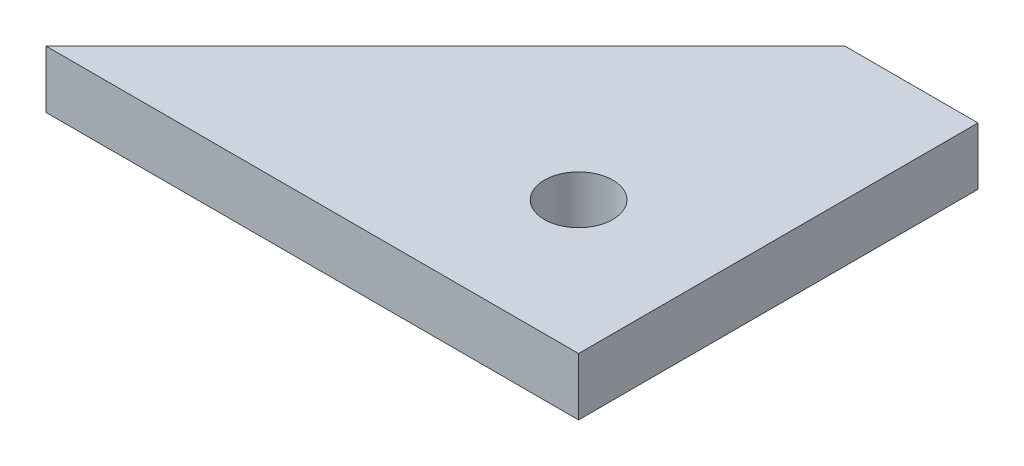
SolidWorks part; units mm, degrees
material "AISI 1020 Steel, Cold Rolled"
ref_plane "Front Plane" through (0, 0, 0) normal (0, 0, 1) x (1, 0, 0)
ref_plane "Top Plane" through (0, 0, 0) normal (0, 1, 0) x (1, 0, 0)
ref_plane "Right Plane" through (0, 0, 0) normal (1, 0, 0) x (0, 0, -1)
sketch "Sketch2" plane through (0, 0, 0) normal (0, 1, 0) x (1, 0, 0)
  line L0 (0, 0) -> (19.05, 19.05)
  line L1 (0, 0) -> (25.4, 0)
  line L4 (25.4, 0) -> (25.4, 19.05)
  line L5 (12.7, 12.7) -> (12.7, 0) construction
  line L6 (12.7, 12.7) -> (25.4, 12.7) construction
  line L7 (12.7, 12.7) -> (25.4, 0) construction
  line L8 (12.7, 0) -> (25.4, 12.7) construction
  line L10 (19.05, 19.05) -> (25.4, 19.05)
  circle A0 centre (19.05, 6.35) radius 1.632
  point P1 (25.0999, 25.0999)
  point P9 (25.4, 22.098)
  point P112 (12.7, 12.7)
  dimension "D1" = 25.4
  dimension "D3" = 19.05
extrude "Boss-Extrude1" add sketch "Sketch2" along normal blind 2.7432
equation "\"D3@Sketch2\"=1-0.25"
